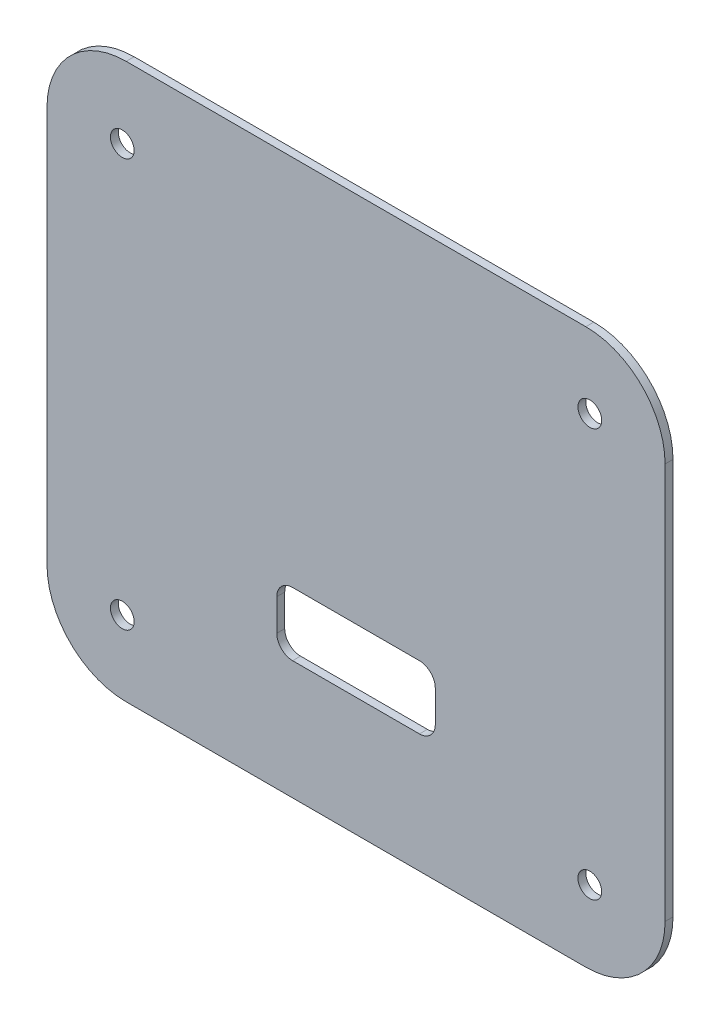
SolidWorks part; units mm, degrees
ref_plane "Front Plane" through (0, 0, 0) normal (0, 0, 1) x (1, 0, 0)
ref_plane "Top Plane" through (0, 0, 0) normal (0, 1, 0) x (1, 0, 0)
ref_plane "Right Plane" through (0, 0, 0) normal (1, 0, 0) x (0, 0, -1)
sketch "Sketch1" plane through (0, 0, 0) normal (0, 0, 1) x (1, 0, 0)
  line L0 (-32.0754, 33.9502) -> (-27.0754, 33.9502)
  line L1 (-24.0754, 24.9502) -> (23.9246, 24.9502)
  line L2 (-24.0754, 24.9502) -> (-24.0754, -15.0498)
  line L3 (-24.0754, -15.0498) -> (23.9246, -15.0498)
  line L4 (23.9246, 24.9502) -> (23.9246, -15.0498)
  line L6 (-10.0754, -15.0498) -> (9.9246, -15.0498)
  line L7 (-39.0754, 39.9502) -> (38.9246, 39.9502)
  line L8 (-39.0754, 39.9502) -> (-39.0754, -30.0498)
  line L9 (-39.0754, -30.0498) -> (38.9246, -30.0498)
  line L10 (38.9246, 39.9502) -> (38.9246, -30.0498)
  line L11 (-10.0754, -15.0498) -> (-10.0754, -7.0498)
  line L12 (-10.0754, -7.0498) -> (9.9246, -7.0498)
  line L13 (-32.0754, -17.5498) -> (-27.0754, -17.5498)
  line L14 (-32.0754, -17.5498) -> (-32.0754, -24.0498)
  line L15 (-32.0754, -24.0498) -> (-27.0754, -24.0498)
  line L16 (-27.0754, -17.5498) -> (-27.0754, -24.0498)
  line L17 (9.9246, -15.0498) -> (9.9246, -7.0498)
  line L19 (-32.0754, 33.9502) -> (-32.0754, 27.4502)
  line L20 (-32.0754, 27.4502) -> (-27.0754, 27.4502)
  line L21 (-27.0754, 33.9502) -> (-27.0754, 27.4502)
  line L22 (26.9246, 33.9502) -> (31.9246, 33.9502)
  line L23 (26.9246, 33.9502) -> (26.9246, 27.4502)
  line L24 (26.9246, 27.4502) -> (31.9246, 27.4502)
  line L25 (31.9246, 33.9502) -> (31.9246, 27.4502)
  line L26 (26.9246, -17.5498) -> (31.9246, -17.5498)
  line L27 (26.9246, -17.5498) -> (26.9246, -24.0498)
  line L28 (26.9246, -24.0498) -> (31.9246, -24.0498)
  line L29 (31.9246, -17.5498) -> (31.9246, -24.0498)
  circle A0 centre (-29.5754, -20.7998) radius 1.5
  circle A1 centre (-29.5754, 30.7002) radius 1.5
  circle A2 centre (29.4246, -20.7998) radius 1.5
  circle A3 centre (29.4246, 30.7002) radius 1.5
  point P0 (0, 0)
  point P6 (0, 0)
  point P11 (-29.5754, -20.7998)
  point P28 (0, 0)
  dimension "D29" = 3
  dimension "D30" = 3
  dimension "D33" = 3
  dimension "D38" = 3
  dimension "D1" = 48
  dimension "D2" = 40
  dimension "D3" = 15
  dimension "D4" = 15
  dimension "D5" = 15
  dimension "D6" = 7
  dimension "D7" = 6.5
  dimension "D8" = 5
  dimension "D9" = 6.5
  dimension "D10" = 5
  dimension "D11" = 5
  dimension "D12" = 6.5
  dimension "D13" = 5
  dimension "D14" = 6.5
  dimension "D15" = 6
  dimension "D16" = 15
  dimension "D17" = 6
  dimension "D18" = 7
  dimension "D19" = 7
  dimension "D20" = 6
  dimension "D21" = 6
  dimension "D22" = 7
  dimension "D23" = 70
  dimension "D24" = 78
  dimension "D25" = 8
  dimension "D26" = 20
  dimension "D27" = 14
  dimension "D28" = 14
  dimension "D31" = 2.5
  dimension "D32" = 3.25
  dimension "D34" = 2.5
  dimension "D35" = 3.25
  dimension "D36" = 2.5
  dimension "D37" = 3.25
  dimension "D39" = 2.5
  dimension "D40" = 3.25
extrude "Boss-Extrude2" add sketch "Sketch1" along normal blind 1 contours L29 L26 L27 L28 A2 | L10 L7 L8 L9 L1 L4 L3 L2 L13 L16 L15 L14 L0 L21 L20 L19 L22 L25 L24 L23 L26 L29 L28 L27 | L16 L13 L14 L15 A0 | L25 L22 L23 L24 A3 | L17 L3 L4 L1 L2 L11 L12 | L21 L0 L19 L20 A1
fillet "Fillet2" radius 10 4 edges at (38.9246, 39.9502, 0.5) (-39.0754, 39.9502, 0.5) (-39.0754, -30.0498, 0.5) (38.9246, -30.0498, 0.5)
fillet "Fillet3" radius 2 4 edges at (9.9246, -15.0498, 0.5) (9.9246, -7.0498, 0.5) (-10.0754, -7.0498, 0.5) (-10.0754, -15.0498, 0.5)
